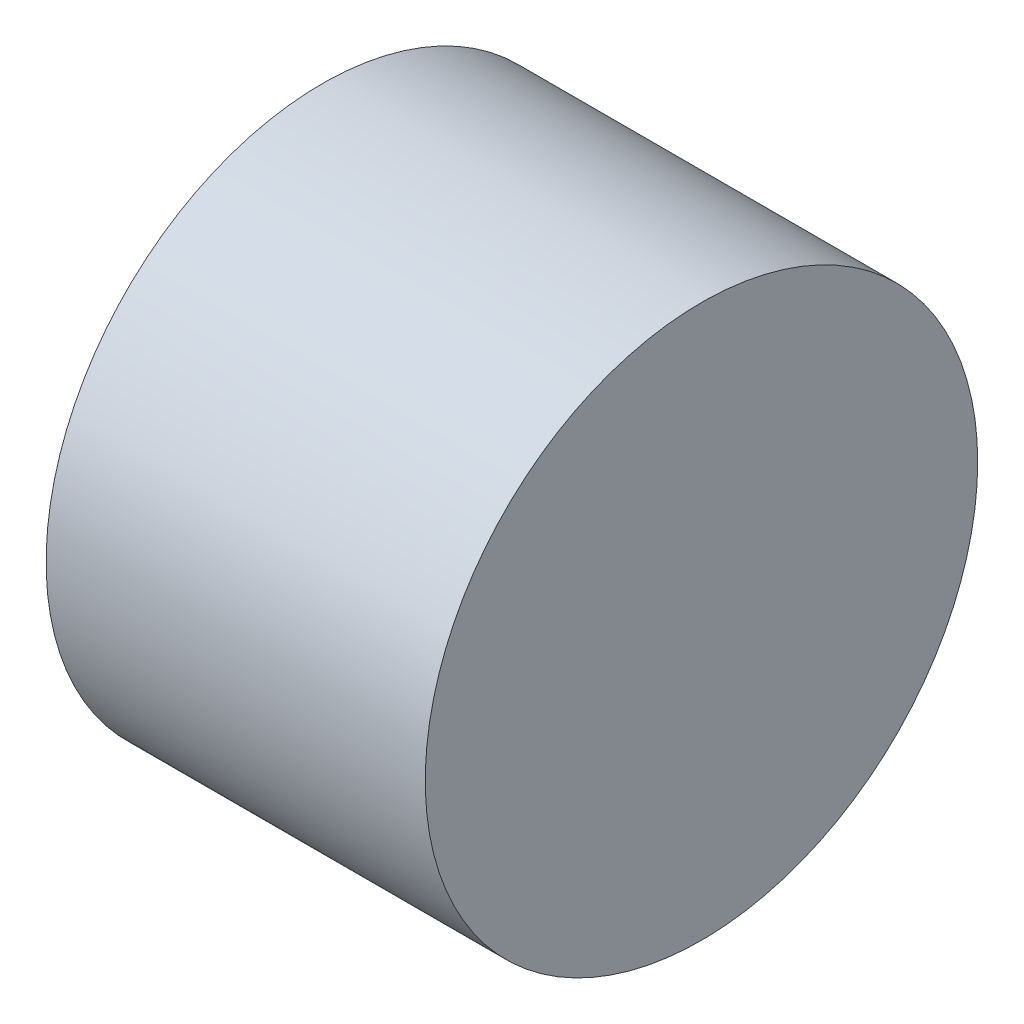
SolidWorks part; units mm, degrees
material "5052-H32"
ref_plane "Front Plane" through (0, 0, 0) normal (0, 0, 1) x (1, 0, 0)
ref_plane "Top Plane" through (0, 0, 0) normal (0, 1, 0) x (1, 0, 0)
ref_plane "Right Plane" through (0, 0, 0) normal (1, 0, 0) x (0, 0, -1)
sketch "Sketch2" plane through (0, 0, 0) normal (1, 0, 0) x (0, 0, -1)
  circle A0 centre (0, 0) radius 25.5 construction
  circle A1 centre (0, 0) radius 25.5
extrude "Boss-Extrude1" add sketch "Sketch2" along normal up to vertex (35 mm away)
